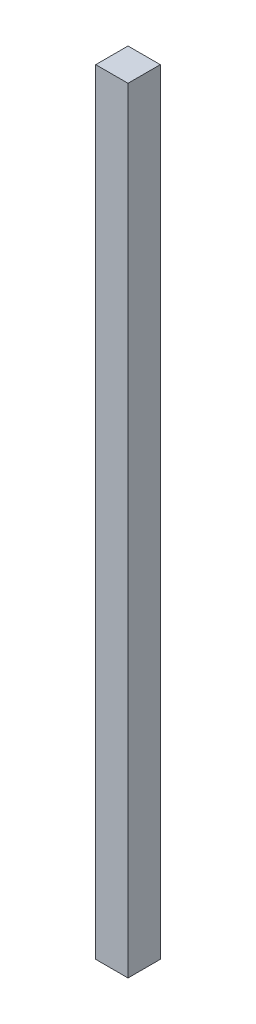
SolidWorks part; units mm, degrees
ref_plane "Front Plane" through (0, 0, 0) normal (0, 0, 1) x (1, 0, 0)
ref_plane "Top Plane" through (0, 0, 0) normal (0, 1, 0) x (1, 0, 0)
ref_plane "Right Plane" through (0, 0, 0) normal (1, 0, 0) x (0, 0, -1)
sketch "Sketch1" plane through (0, 0, 0) normal (0, 1, 0) x (1, 0, 0)
  line L1 (0, 0) -> (25.4, 0)
  line L2 (0, 0) -> (0, 25.4)
  line L3 (0, 25.4) -> (25.4, 25.4)
  line L4 (25.4, 0) -> (25.4, 25.4)
  dimension "D1" = 25.4
  dimension "D2" = 25.4
extrude "Boss-Extrude1" add sketch "Sketch1" along normal blind 609.6
